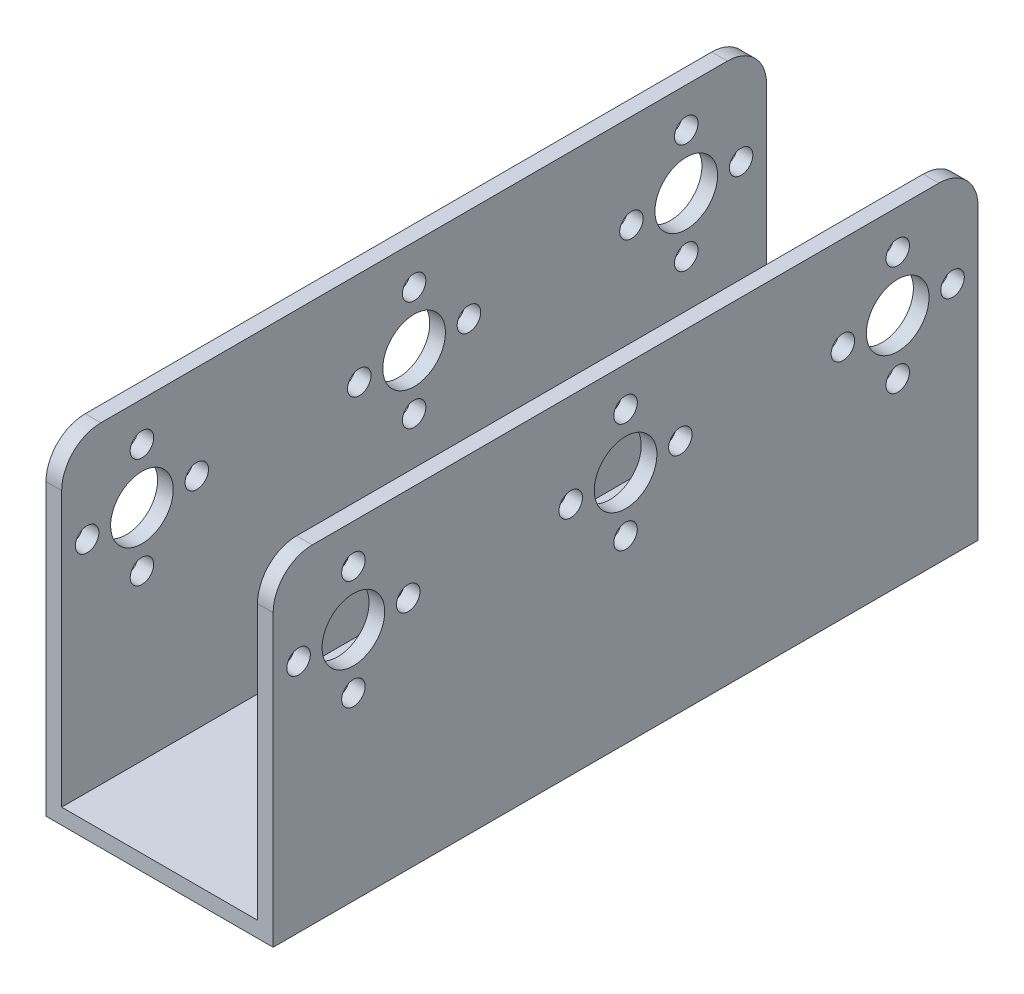
SolidWorks part; units mm, degrees
ref_plane "前视基准面" through (0, 0, 0) normal (0, 0, 1) x (1, 0, 0)
ref_plane "上视基准面" through (0, 0, 0) normal (0, 1, 0) x (1, 0, 0)
ref_plane "右视基准面" through (0, 0, 0) normal (1, 0, 0) x (0, 0, -1)
other "Configuration Table"
sketch "草图1" plane through (0, 0, 0) normal (0, 0, 1) x (1, 0, 0)
  line L0 (-14.5, 40) -> (-14.5, -2)
  line L1 (-14.5, -2) -> (14.5, -2)
  line L2 (14.5, -2) -> (14.5, 40)
  line L3 (14.5, 40) -> (12.5, 40)
  line L4 (12.5, 40) -> (12.5, 0)
  line L5 (12.5, 0) -> (-12.5, 0)
  line L6 (-12.5, 0) -> (-12.5, 40)
  line L7 (-12.5, 40) -> (-14.5, 40)
  point P11 (0, 0)
  point P12 (-12.5, -9.302)
  point P13 (0, 0)
  point P14 (0, 0)
  dimension "D1" = 2
  dimension "D2" = 2
  dimension "D3" = 25
  dimension "D4" = 42
  dimension "D5" = 2
extrude "凸台-拉伸1" add sketch "草图1" against normal blind 90
sketch "草图2" plane through (14.5, 0, 0) normal (1, 0, 0) x (0, 0, -1)
  line L0 (90, -2) -> (0, -2) construction
  line L1 (45, 40) -> (45, -2) construction
  line L2 (90, 40) -> (0, 40) construction
  circle A0 centre (79.75, 28) radius 4
  circle A1 centre (79.75, 35) radius 1.5
  circle A2 centre (86.75, 28) radius 1.5
  circle A3 centre (79.75, 21) radius 1.5
  circle A4 centre (72.75, 28) radius 1.5
  arc A5 (72.75, 28) -> (86.75, 28) centre (79.75, 28) cw construction
  circle A6 centre (10.25, 21) radius 1.5
  circle A7 centre (3.25, 28) radius 1.5
  circle A8 centre (10.25, 35) radius 1.5
  circle A9 centre (10.25, 28) radius 4
  circle A10 centre (17.25, 28) radius 1.5
  circle A11 centre (45, 28) radius 4
  circle A12 centre (45, 35) radius 1.5
  circle A13 centre (52, 28) radius 1.5
  circle A14 centre (45, 21) radius 1.5
  circle A15 centre (38, 28) radius 1.5
  arc A16 (38, 28) -> (52, 28) centre (45, 28) cw construction
  point P10 (0, 0)
  point P11 (0, 0)
  point P18 (79.75, 28)
  point P19 (0, 0)
  point P20 (0, 0)
  point P21 (0, 0)
  point P22 (78.7413, 28)
  point P23 (78.7413, 27.3755)
  point P24 (78.4455, 28)
  point P45 (45, 28)
  point P46 (44.7822, 29.1095)
  point P47 (0, 0)
  point P48 (45.0996, 30.0616)
  point P49 (44.2934, 30.2218)
  point P50 (45, 30.654)
  point P51 (45, 29.5403)
  point P52 (0, 0)
  point P53 (0, 0)
  dimension "D1" = 30
  dimension "D2" = 8
  dimension "D3" = 3
  dimension "D5" = 7
  dimension "D6" = 8
  dimension "D7" = 3
  dimension "D8" = 7
  dimension "D10" = 34.75
  dimension "D11" = 3
  dimension "D12" = 3
  dimension "D13" = 3
  dimension "D9" = 7
  dimension "D4" = 4
extrude "切除-拉伸1" cut sketch "草图2" against normal blind 90
fillet "圆角1" radius 5 4 edges at (13.5, 40, -90) (-13.5, 40, -90) (-13.5, 40, 0) (13.5, 40, 0)
